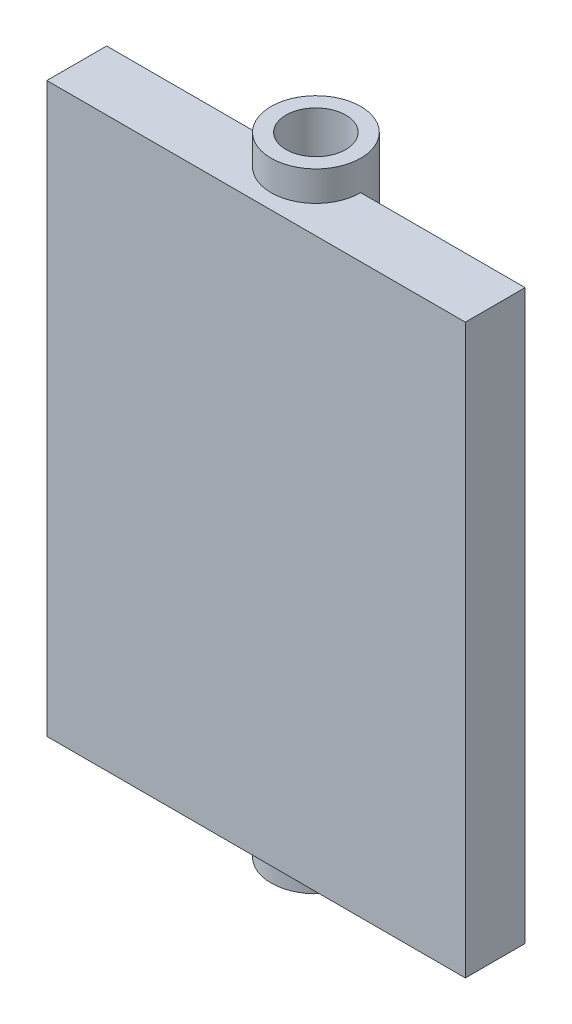
SolidWorks part; units mm, degrees
material "6063-T6"
ref_plane "X-Y Datum" through (0, 0, 0) normal (0, 0, 1) x (1, 0, 0)
ref_plane "X-Z Datum" through (0, 0, 0) normal (0, 1, 0) x (1, 0, 0)
ref_plane "Y-Z Datum" through (0, 0, 0) normal (1, 0, 0) x (0, 0, -1)
sketch "Sketch1" plane through (0, 0, 0) normal (0, 1, 0) x (1, 0, 0)
  circle A0 centre (0, 0) radius 9.525
  circle A1 centre (0, 0) radius 6.35
  dimension "D1" = 19.05
  dimension "D2" = 12.7
extrude "Boss-Extrude1" add sketch "Sketch1" along normal mid plane 133.35
sketch "Sketch2" plane through (0, 0, 0) normal (0, 1, 0) x (1, 0, 0)
  line L0 (9.525, 0) -> (44.45, 0)
  line L1 (-44.45, 0) -> (-9.525, 0)
  line L2 (-44.45, 0) -> (-44.45, -12.7)
  line L3 (-44.45, -12.7) -> (44.45, -12.7)
  line L4 (44.45, 0) -> (44.45, -12.7)
  arc A0 (-9.525, 0) -> (9.525, 0) centre (0, 0) ccw
  circle A1 centre (0, 0) radius 9.525 construction
  point P8 (0, -12.7)
  point P11 (-9.4331, -1.3196)
  point P12 (0, 0)
  dimension "D1" = 12.7
  dimension "D2" = 88.9
extrude "Boss-Extrude2" add sketch "Sketch2" along normal mid plane 120.65
